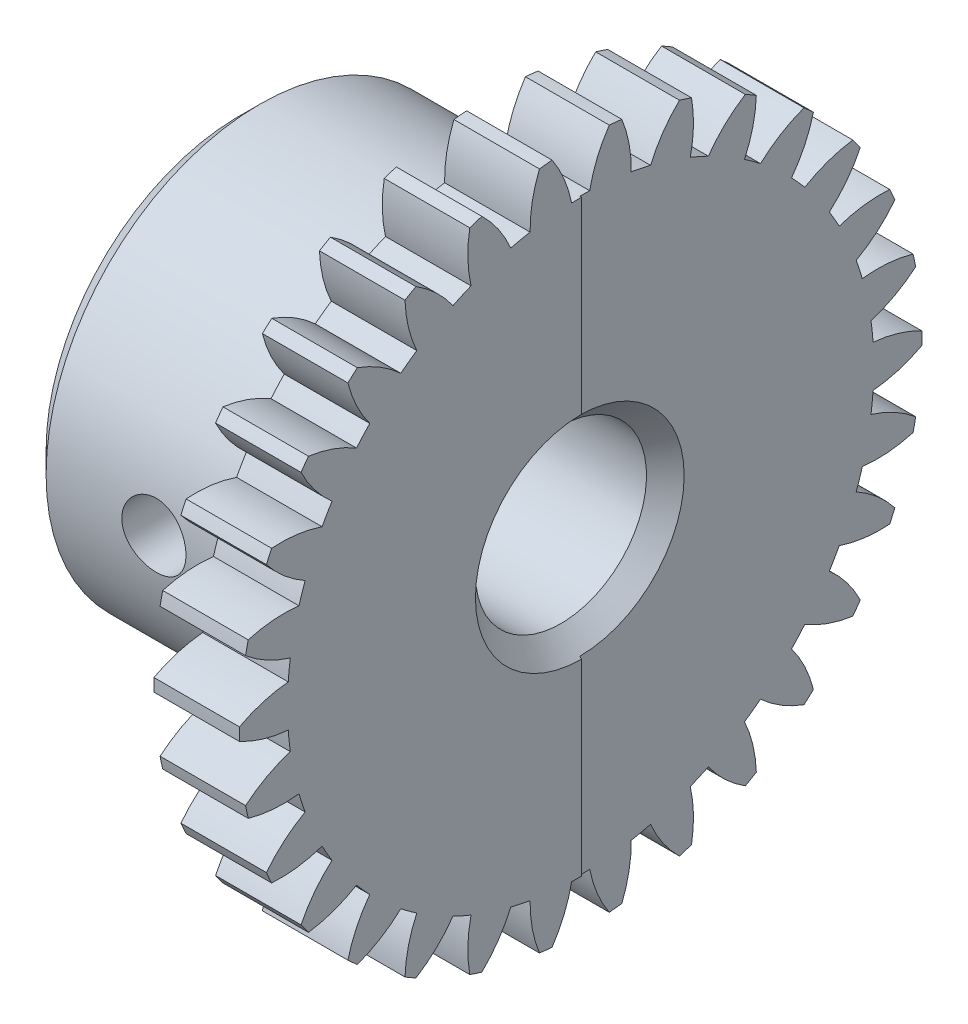
SolidWorks part; units mm, degrees
material "AISI 316 Stainless Steel Sheet (SS)"
ref_plane "Plane1" through (0, 0, 0) normal (0, 0, 1) x (1, 0, 0)
ref_plane "Plane2" through (0, 0, 0) normal (0, 1, 0) x (1, 0, 0)
ref_plane "Plane3" through (0, 0, 0) normal (1, 0, 0) x (0, 0, -1)
sketch "HoldingSke" plane through (0, 0, 0) normal (0, 1, 0) x (1, 0, 0)
  line L0 (0, 0) -> (351.9527, -203.2)
  line L1 (-15, 0) -> (100, 0) construction
  line L2 (0, 0) -> (-2.1039, 2.3779)
  line L3 (0, 0) -> (-11.863, 4.5341)
  line L4 (0, 0) -> (7.479, 4.318)
  line L5 (0, 0) -> (-23.7986, -8.8762)
  line L6 (0, 0) -> (-5.2639, -3.5516)
  line L7 (-2.1039, 2.3779) -> (3.3635, 27.1825)
  line L8 (-76.2, 54.61) -> (-61.976, 54.61)
  line L9 (-71.009, 38.7566) -> (-53.1078, 45.2721)
  line L10 (-76.2, 71.12) -> (104.1128, 71.12)
  line L11 (0, 0) -> (-6.35, 0)
  line L12 (-76.2, 101.6) -> (-76.1428, 101.6)
  line L13 (24.9733, 27.94) -> (52.9518, 28.4284)
  line L14 (24.9733, 27.94) -> (24.9746, 27.94)
  line L15 (24.9733, 27.94) -> (100.4006, 29.5858)
  circle A0 centre (0, 0) radius 6.35
  circle A1 centre (0, 0) radius 15.875
  circle A2 centre (0, 0) radius 15.875
  circle A3 centre (0, 0) radius 6.35
  dimension "MHD" = 31.75
  dimension "Hub_dia" = 31.75
  dimension "Bore" = 12.7
  dimension "MBD" = 12.7
  dimension "Num_teeth" = 30
  dimension "Pitch" = 406.4
  dimension "Overall_len" = 25.4
  dimension "Show_teeth" = 30
  dimension "Thickness" = 6.35
  dimension "OAL" = 25.4001
  dimension "T_dim" = 14.224
  dimension "Ap" = 20
  dimension "H" = 19.05
  dimension "Pitch_radius" = 180.3128
  dimension "Width" = 6.35
  dimension "Backlash" = 0.0571
  dimension "Addendum_fac" = 1
  dimension "Dedendum_fac" = 1.25
  dimension "Clearance_fac" = 0.25
  dimension "Dedendum_add" = 0.0013
sketch "BasProSke" plane through (0, 0, 0) normal (0, 1, 0) x (1, 0, 0)
  line L0 (-10, 0) -> (60, 0) construction
  line L1 (0, 0) -> (0, 25.4)
  line L2 (0, 0) -> (6.35, 0)
  line L3 (6.35, 0) -> (6.35, 25.4)
  line L4 (6.35, 25.4) -> (0, 25.4)
  dimension "Thickness" = 6.35
  dimension "Diameter" = 50.8
revolve "Base-Revolve" add sketch "BasProSke" angle 360 about L0
sketch "TooCutSke" plane through (0, 0, 0) normal (1, 0, 0) x (0, 0, -1)
  line L1 (0, 0) -> (0, 107) construction
  line L2 (0, 0) -> (-1.3462, 23.7744) construction
  line L3 (0, 0) -> (-4.9724, 47.3092) construction
  line L4 (-1.3462, 23.7744) -> (-2.4862, 23.6546) construction
  arc A0 (0.7354, 21.8145) -> (-0.7354, 21.8145) centre (0, 0) ccw
  arc A1 (2.2029, 25.3298) -> (-2.2029, 25.3298) centre (0, 0) ccw
  circle A2 centre (0, 0) radius 23.8125 construction
  circle A3 centre (0, 0) radius 22.3764 construction
  arc A4 (-0.7354, 21.8145) -> (-2.2029, 25.3298) centre (-10.0814, 19.9767) ccw
  arc A5 (2.2029, 25.3298) -> (0.7354, 21.8145) centre (10.0814, 19.9767) ccw
  dimension "Root_dia" = 43.6537
  dimension "Overcut_dia" = 50.8508
  dimension "Pitch_dia" = 47.625
  dimension "Base_dia" = 44.7529
  dimension "Flank_rad" = 9.525
  dimension "Half_ang" = 6
  dimension "Half_CT" = 1.1462
extrude "ToothCut" cut sketch "TooCutSke" along normal through all
fillet "Breaks" [suppressed] radius 0.0318
fillet "RootFillets" [suppressed] radius 0.3981
pattern_circular "TeethCuts" count 30 every 12 about axis through (-10, 0, 0) along (1, 0, 0) of "ToothCut", "RootFillets", "Breaks"
sketch "HubNeaOneSke" plane through (0, 0, 0) normal (-1, 0, 0) x (0, 0, 1)
  circle A0 centre (0, 0) radius 15.875
  dimension "Diameter" = 31.75
extrude "HubNearOne" add sketch "HubNeaOneSke" along normal blind 19.0501
sketch "HubNeaBotSke" plane through (0, 0, 0) normal (-1, 0, 0) x (0, 0, 1)
  circle A0 centre (0, 0) radius 15.875
  dimension "Diameter" = 31.75
extrude "HubNearBoth" [suppressed] add sketch "HubNeaBotSke" along normal blind 9.525
ref_plane "FarPln" through (6.35, 0, 0) normal (1, 0, 0) x (0, 0, -1)
sketch "HubFarSke" plane through (6.35, 0, 0) normal (1, 0, 0) x (0, 0, -1)
  circle A0 centre (0, 0) radius 15.875
  dimension "Diameter" = 31.75
extrude "HubFar" [suppressed] add sketch "HubFarSke" along normal blind 9.525
sketch "BorSke" plane through (0, 0, 0) normal (1, 0, 0) x (0, 0, -1)
  circle A0 centre (0, 0) radius 6.35
  dimension "Diameter" = 12.7
extrude "Bore" cut sketch "BorSke" along normal mid plane 50.8001
sketch "KeySke" plane through (0, 0, 0) normal (1, 0, 0) x (0, 0, -1)
  line L0 (-1.5875, 0) -> (-1.5875, 7.874)
  line L1 (-1.5875, 7.874) -> (1.5875, 7.874)
  line L2 (1.5875, 7.874) -> (1.5875, 0)
  line L3 (0, 0) -> (0, 34) construction
  line L4 (-1.5875, 0) -> (1.5875, 0)
  dimension "Offset" = 7.874
  dimension "Width" = 3.175
extrude "Keyway" [suppressed] cut sketch "KeySke" along normal mid plane 50.8001
pattern_circular "Keyway2" [suppressed] count 2 every 90 about axis through (-10, 0, 0) along (1, 0, 0)
chamfer "Chamfer1" distance 1.524 angle 45 2 edges at (0, 0, -15.875) (-19.0501, 0, 15.875)
chamfer "Chamfer2" distance 1.524 angle 45 2 edges at (6.35, 0, 6.35) (-19.0501, 0, 6.35)
sketch "Sketch1" plane through (0, 0, 0) normal (0, 0, 1) x (1, 0, 0)
  line L0 (-17.5261, 0) -> (-1.524, 0) construction
  line L1 (-17.5261, -15.875) -> (-17.5261, 15.875) construction
  line L2 (-1.524, -15.875) -> (-1.524, 15.875) construction
  circle A0 centre (-9.525, 0) radius 2.3813
  dimension "D1" = 4.7625
extrude "Cut-Extrude1" cut sketch "Sketch1" against normal through all and the other way through all
sketch "Sketch2" plane through (6.35, 0, 0) normal (1, 0, 0) x (0, 0, -1)
  line L0 (0, -28.9882) -> (0, 34.9728)
  line L1 (0, 34.9728) -> (32.2299, 34.9728)
  line L2 (32.2299, 34.9728) -> (32.2299, -28.9882)
  line L3 (32.2299, -28.9882) -> (0, -28.9882)
  dimension "D1" = 32.2299
  dimension "D2" = 63.961
  dimension "D3" = 34.9728
extrude "Cut-Extrude2" cut sketch "Sketch2" against normal blind 0.127
equation "' \"Pitch@HoldingSke\" = 4"
equation "' \"Num_teeth@HoldingSke\" = 12"
equation "' \"Ap@HoldingSke\" =  20"
equation "' \"Ap@HoldingSke\" = 20"
equation "' \"Width@HoldingSke\" = 0.5"
equation "' \"Hub_dia@HoldingSke\"= 1"
equation "' \"Hub_dia@HoldingSke\" = 1"
equation "' \"Overall_len@HoldingSke\" = 1.0"
equation "' \"Bore@HoldingSke\" = 0.75"
equation "' \"T_dim@HoldingSke\" = 0.85"
equation "' \"Width@KeySke\" = 0.25"
equation "' \"Show_teeth@HoldingSke\" = 13"
equation "' \"Backlash@HoldingSke\" = 0.009"
equation "' \"Addendum_fac@HoldingSke\" = 1.0"
equation "' \"Dedendum_fac@HoldingSke\" = 1.25"
equation "' \"Dedendum_add@HoldingSke\" = 0.00005"
equation "' \"Clearance_fac@HoldingSke\" = 0.25"
equation "' \"Pitch@HoldingSke\" = 0.5"
equation "' \"Num_teeth@HoldingSke\" = 23"
equation "' \"Show_teeth@HoldingSke\" = 23"
equation "' \"Backlash@HoldingSke\" = 0.0375"
equation "\"Overcut_dia@TooCutSke\" = (\"Num_teeth@HoldingSke\" + 2 * \"Addendum_fac@HoldingSke\") / \"Pitch@HoldingSke\" + 0.002"
equation "\"Pitch_dia@TooCutSke\" = \"Num_teeth@HoldingSke\" / \"Pitch@HoldingSke\""
equation "\"Base_dia@TooCutSke\" = \"Num_teeth@HoldingSke\" / \"Pitch@HoldingSke\" * cos((\"Ap@HoldingSke\"  * 3.14159265 / 180))"
equation "\"Root_dia@TooCutSke\" = (\"Num_teeth@HoldingSke\" + 2) / \"Pitch@HoldingSke\" - 2 * (\"Addendum_fac@HoldingSke\" + \"Dedendum_fac@HoldingSke\") / \"Pitch@HoldingSke\" - \"Dedendum_add@HoldingSke\" * 2"
equation "\"Half_ang@TooCutSke\" = 180 / \"Num_teeth@HoldingSke\""
equation "\"Half_CT@TooCutSke\" = \"Num_teeth@HoldingSke\" / \"Pitch@HoldingSke\" * sin((3.14159265 / 2 / \"Num_teeth@HoldingSke\")) / 2 - 7 * \"Backlash@HoldingSke\" / 4"
equation "\"Flank_rad@TooCutSke\" = \"Num_teeth@HoldingSke\" / \"Pitch@HoldingSke\" / 5"
equation "\"Radius@RootFillets\" = \"Clearance_fac@HoldingSke\" / \"Pitch@HoldingSke\" + \"Dedendum_add@HoldingSke\""
equation "\"Break_rad@Breaks\" = 0.02 / \"Pitch@HoldingSke\""
equation "\"Thickness@HoldingSke\" = \"Width@HoldingSke\""
equation "\"OAL@HoldingSke\" = \"Thickness@HoldingSke\""
equation "\"MHD@HoldingSke\" = (\"Num_teeth@HoldingSke\" + 2) / \"Pitch@HoldingSke\" - 2 * (\"Addendum_fac@HoldingSke\" + \"Dedendum_fac@HoldingSke\")  / \"Pitch@HoldingSke\" - \"Dedendum_add@HoldingSke\" * 2"
equation "\"MBD@HoldingSke\" = (\"Num_teeth@HoldingSke\" + 2) / \"Pitch@HoldingSke\" - 2 * (\"Addendum_fac@HoldingSke\" + \"Dedendum_fac@HoldingSke\")  / \"Pitch@HoldingSke\" - \"Dedendum_add@HoldingSke\" * 2 - 0.002"
equation "\"MHD@HoldingSke\" = ((sgn( \"MHD@HoldingSke\" - \"Hub_dia@HoldingSke\" )-1)*( \"MHD@HoldingSke\" - \"Hub_dia@HoldingSke\" ))/-2+ \"Hub_dia@HoldingSke\""
equation "\"MBD@HoldingSke\" = ((sgn( \"MBD@HoldingSke\" - \"Bore@HoldingSke\" )-1)*( \"MBD@HoldingSke\" - \"Bore@HoldingSke\" ))/-2+ \"Bore@HoldingSke\""
equation "\"OAL@HoldingSke\" = ((sgn( \"OAL@HoldingSke\" - \"Overall_len@HoldingSke\" )+1)*( \"OAL@HoldingSke\" - \"Overall_len@HoldingSke\" ))/2 + \"Overall_len@HoldingSke\" + 0.000002"
equation "\"Num_teeth@TeethCuts\" = int( \"Show_teeth@HoldingSke\" ) + 1"
equation "\"Num_teeth@TeethCuts\" = ((sgn( \"Num_teeth@TeethCuts\" - \"Num_teeth@HoldingSke\" )-1)*( \"Num_teeth@TeethCuts\" - \"Num_teeth@HoldingSke\" ))/-2+ \"Num_teeth@HoldingSke\""
equation "\"Num_teeth@TeethCuts\" = ((sgn( \"Num_teeth@TeethCuts\" - 2.0)+1)*( \"Num_teeth@TeethCuts\" - 2.0))/2 +2.0"
equation "\"Angle@TeethCuts\" = 360.0 / \"Num_teeth@HoldingSke\""
equation "\"Diameter@BasProSke\" = (\"Num_teeth@HoldingSke\" + 2 * \"Addendum_fac@HoldingSke\") / \"Pitch@HoldingSke\""
equation "\"Thickness@BasProSke\"  = \"Thickness@HoldingSke\""
equation "' \"Fillet_rad@BasProSke\" =  \"Thickness@HoldingSke\" * 0.05"
equation "' \"Fillet_rad@BasProSke\" = \"Thickness@HoldingSke\" * 0.05"
equation "\"MHD@HoldingSke\" = ((sgn( \"MHD@HoldingSke\" - \"Root_dia@TooCutSke\" )-1)*( \"MHD@HoldingSke\" - \"Root_dia@TooCutSke\" ))/-2+ \"Root_dia@TooCutSke\""
equation "\"Diameter@HubNeaOneSke\" = \"MHD@HoldingSke\""
equation "\"Length@HubNearOne\" = \"OAL@HoldingSke\" - \"Thickness@BasProSke\""
equation "\"Diameter@HubNeaBotSke\" = \"MHD@HoldingSke\""
equation "\"Length@HubNearBoth\" = ( \"OAL@HoldingSke\" - \"Thickness@BasProSke\" ) / 2.0"
equation "\"Thickness@FarPln\" = \"Thickness@BasProSke\""
equation "\"Diameter@HubFarSke\" = \"MHD@HoldingSke\""
equation "\"Length@HubFar\" = ( \"OAL@HoldingSke\" - \"Thickness@BasProSke\" ) / 2.0"
equation "\"Diameter@BorSke\" = \"MBD@HoldingSke\""
equation "\"D1@Bore\" = \"OAL@HoldingSke\" * 2.0"
equation "\"D1@Keyway\" = \"OAL@HoldingSke\" * 2.0"
equation "\"Offset@KeySke\" = \"T_dim@HoldingSke\" - \"MBD@HoldingSke\" / 2.0"
